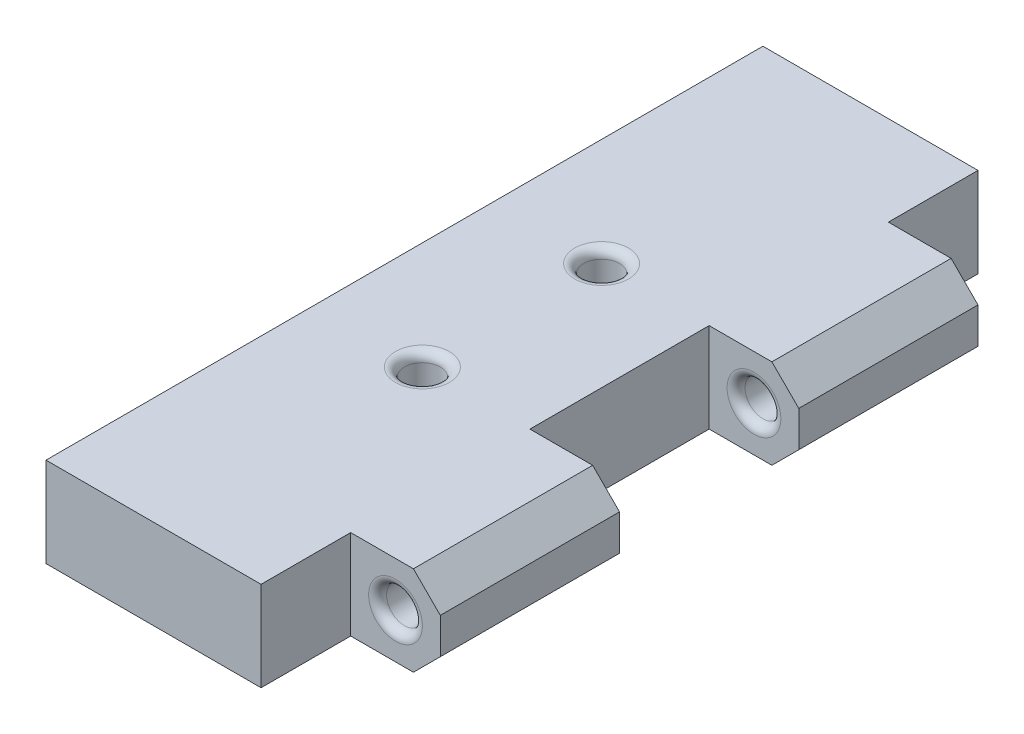
SolidWorks part; units mm, degrees
ref_plane "Front Plane" through (0, 0, 0) normal (0, 0, 1) x (1, 0, 0)
ref_plane "Top Plane" through (0, 0, 0) normal (0, 1, 0) x (1, 0, 0)
ref_plane "Right Plane" through (0, 0, 0) normal (1, 0, 0) x (0, 0, -1)
sketch "Sketch1" plane through (0, 0, 0) normal (0, 1, 0) x (1, 0, 0)
  line L0 (-6, 0) -> (6, 0) construction
  line L1 (6, -20) -> (-6, -20)
  line L2 (6, -20) -> (6, 20)
  line L3 (6, 20) -> (-6, 20)
  line L4 (-6, -20) -> (-6, 20)
  line L5 (6, -20) -> (-6, 20) construction
  line L6 (6, 20) -> (-6, -20) construction
  line L7 (0, -5) -> (0, 5) construction
  circle A0 centre (0, 5) radius 1
  circle A1 centre (0, -5) radius 1
  point P0 (0, 0)
  dimension "D3" = 5
  dimension "D4" = 2
  dimension "D1" = 40
  dimension "D2" = 12
extrude "Hinge " add sketch "Sketch1" along normal blind 5
sketch "Sketch2" plane through (6, 0, 0) normal (1, 0, 0) x (0, 0, -1)
  line L0 (0, 0) -> (0, 5) construction
  line L1 (-20, 0) -> (20, 0) construction
  line L2 (-20, 5) -> (20, 5) construction
  line L3 (-20, 2.5) -> (20, 2.5) construction
  line L4 (-20, 5) -> (-20, 0) construction
  line L5 (20, 5) -> (20, 0) construction
  line L7 (-5, 0) -> (-15, 0)
  line L8 (-5, 0) -> (-5, 5)
  line L9 (-5, 5) -> (-15, 5)
  line L10 (-15, 0) -> (-15, 5)
  line L11 (-5, 0) -> (-15, 5) construction
  line L12 (-5, 5) -> (-15, 0) construction
  line L13 (15, 0) -> (5, 0)
  line L14 (15, 0) -> (15, 5)
  line L15 (15, 5) -> (5, 5)
  line L16 (5, 0) -> (5, 5)
  line L17 (15, 0) -> (5, 5) construction
  line L18 (15, 5) -> (5, 0) construction
  point P12 (-10, 2.5)
  point P17 (10, 2.5)
  dimension "D1" = 5
  dimension "D2" = 5
  dimension "D3" = 10
extrude "Hinge Extrude 1" add sketch "Sketch2" along normal blind 5
sketch "Sketch3" plane through (0, 0, -15) normal (0, 0, -1) x (-1, 0, 0)
  line L0 (-8.5, 0) -> (-8.5, 5) construction
  line L1 (-11, 0) -> (-6, 0) construction
  line L2 (-11, 5) -> (-6, 5) construction
  circle A0 centre (-8.5, 2.5) radius 1
  dimension "D1" = 2
extrude "Hole Cut 1" cut sketch "Sketch3" against normal through all both and the other way through all
fillet "Fillet Holes 1" radius 0.5 8 edges at (9.5, 2.5, -15) (7.5, 2.5, -5) (9.5, 2.5, 5) (7.5, 2.5, 15) (0, 5, 6) (0, 0, 6) (0, 5, -4) (0, 0, -4)
chamfer "Chamfer 1" distance 1.5 angle 45 4 edges at (11, 5, -10) (11, 0, -10) (11, 0, 10) (11, 5, 10)
sketch "Sketch4" [suppressed] plane through (6, 0, 0) normal (1, 0, 0) x (0, 0, -1)
  line L0 (0, 0) -> (0, 5) construction
  line L1 (-20, 0) -> (20, 0) construction
  line L2 (-20, 5) -> (20, 5) construction
  line L4 (5, 0) -> (-5, 0)
  line L5 (5, 0) -> (5, 5)
  line L6 (5, 5) -> (-5, 5)
  line L7 (-5, 0) -> (-5, 5)
  line L8 (5, 0) -> (-5, 5) construction
  line L9 (5, 5) -> (-5, 0) construction
  point P6 (0, 2.5)
  dimension "D1" = 5
  dimension "D2" = 10
extrude "Hinge Extrude 2" [suppressed] add sketch "Sketch4" along normal blind 5
sketch "Sketch6" [suppressed] plane through (0, 0, -5) normal (0, 0, -1) x (-1, 0, 0)
  line L0 (-8.5, 0) -> (-8.5, 5) construction
  line L1 (-11, 0) -> (-6, 0) construction
  line L2 (-11, 5) -> (-6, 5) construction
  circle A0 centre (-8.5, 2.5) radius 1
  dimension "D1" = 2
extrude "Hole Cut 2 " [suppressed] cut sketch "Sketch6" against normal through all
chamfer "Chamfer2" [suppressed] distance 1.5 angle 45
fillet "Fillet Holes 2" [suppressed] radius 0.5
sketch "Sketch7" [suppressed] plane through (0, 0, 0) normal (0, 0, 1) x (1, 0, 0)
  circle A0 centre (0, 0) radius 1
  dimension "D1" = 2
extrude "Hinge Bar" [suppressed] add sketch "Sketch7" along normal blind 42
sketch "Sketch8" [suppressed] plane through (0, 0, 0) normal (0, 0, -1) x (-1, 0, 0)
  circle A0 centre (0, 0) radius 1.5
  dimension "D1" = 3
extrude "Hinge Bar Holder" [suppressed] add sketch "Sketch8" along normal blind 1
chamfer "Hinge Bar Holder Fillet" [suppressed] distance 0.5 angle 45
sketch "Sketch9" [suppressed] plane through (0, 0, 0) normal (1, 0, 0) x (0, 0, -1)
  circle A0 centre (0, 0) radius 1.5
  dimension "D1" = 3
extrude "Hinge Bar Cap" [suppressed] add sketch "Sketch9" along normal blind 2
chamfer "Hinge Bar Cap Fillet" [suppressed] distance 0.5 angle 45
sketch "Sketch10" [suppressed] plane through (2, 0, 0) normal (1, 0, 0) x (0, 0, -1)
  circle A0 centre (0, 0) radius 1
  dimension "D1" = 2
extrude "Hinge Bar Cap Cut" [suppressed] cut sketch "Sketch10" against normal blind 1
sketch "Sketch11" [suppressed] plane through (0, 0, 0) normal (0, 0, 1) x (1, 0, 0)
  line L1 (-33, 20) -> (33, 20)
  line L2 (-33, 20) -> (-33, -20)
  line L3 (-33, -20) -> (33, -20)
  line L4 (33, 20) -> (33, -20)
  line L5 (-33, 20) -> (33, -20) construction
  line L6 (-33, -20) -> (33, 20) construction
  point P0 (0, 0)
  dimension "D1" = 40
  dimension "D2" = 66
extrude "Hole Side Thing" [suppressed] add sketch "Sketch11" along normal blind 3.2
sketch "Sketch12" [suppressed] plane through (0, 0, 3.2) normal (0, 0, 1) x (1, 0, 0)
  line L0 (0, 0) -> (-33, 0) construction
  line L1 (-33, 20) -> (-33, -20) construction
  circle A0 centre (-22, 7) radius 1
  circle A1 centre (-22, -7) radius 1
  dimension "D1" = 2
  dimension "D3" = 11
  dimension "D2" = 7
extrude "Holes for Hole Side Thing" [suppressed] cut sketch "Sketch12" against normal blind 3.2
